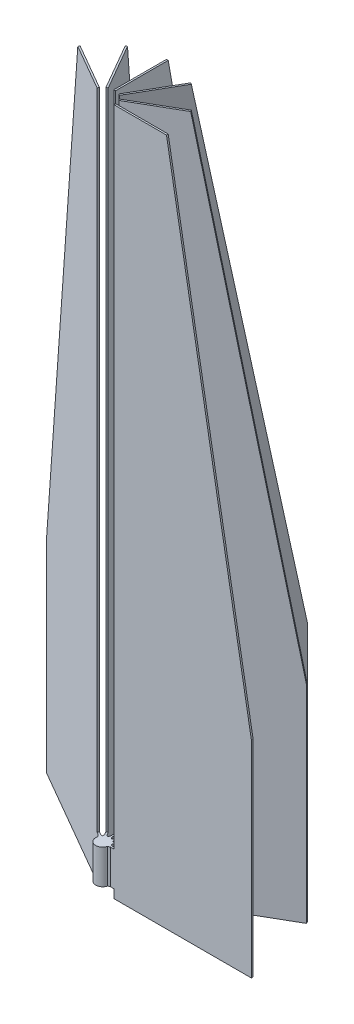
SolidWorks part; units mm, degrees
material "自定义塑料"
ref_plane "前视基准面" through (0, 0, 0) normal (0, 0, 1) x (1, 0, 0)
ref_plane "上视基准面" through (0, 0, 0) normal (0, 1, 0) x (1, 0, 0)
ref_plane "右视基准面" through (0, 0, 0) normal (1, 0, 0) x (0, 0, -1)
other "Configuration Table"
sketch "Sketch1" plane through (0, 0, 0) normal (0, 0, 1) x (1, 0, 0)
  line L0 (0, 0) -> (0, 20)
  line L1 (0, 20) -> (2, 20)
  line L2 (2, 20) -> (2, 395)
  line L3 (2, 395) -> (32.6284, 395)
  line L4 (32.6284, 395) -> (82, 115)
  line L5 (82, 115) -> (82, -5)
  line L6 (82, -5) -> (2, -5)
  line L7 (2, -5) -> (2, 0)
  line L8 (2, 0) -> (0, 0)
  point P11 (1, 0)
  dimension "D1" = 20
  dimension "D2" = 5
  dimension "D3" = 400
  dimension "D4" = 80
  dimension "D5" = 100
  dimension "D6" = 2
  dimension "D7" = 120
extrude "Boss-Extrude1" add sketch "Sketch1" along normal blind 1
sketch "Sketch2" plane through (0, -5, 0) normal (0, -1, 0) x (1, 0, 0)
  line L0 (0, 1) -> (0, 0) construction
  line L1 (0, 1) -> (2, 1) construction
  circle A0 centre (-5, 0.5) radius 4
  dimension "D1" = 8
  dimension "D2" = 5
  dimension "D3" = 0.5
extrude "Boss-Extrude2" add sketch "Sketch2" against normal blind 20 from surface at -5 separate body starting at face at (1, 0, 0.5)
sketch "Sketch3" plane through (0, 0, 0) normal (0, -1, 0) x (1, 0, 0)
  line L0 (0, 1) -> (-1.1363, 1.5353)
  line L1 (0, 0) -> (0, 1)
  line L2 (0, 0) -> (-1.1363, -0.5353)
  line L3 (-5, 0.5) -> (0, 0.5) construction
  line L4 (-1.1363, 1.5353) -> (-5, 0.5) construction
  line L5 (-5, 0.5) -> (-1.1363, -0.5353) construction
  arc A0 (-1.1363, -0.5353) -> (-1.1363, 1.5353) centre (-5, 0.5) ccw
  dimension "D1" = 15
  dimension "D2" = 15
extrude "Boss-Extrude3" add sketch "Sketch3" against normal blind 20
pattern_circular "CirPattern1" count 6 every 30 about axis through (-5, 0, 0.5) along (0, 1, 0) of "Boss-Extrude3"
pattern_circular "CirPattern2" count 7 every 30 about axis through (-5, 0, 0.5) along (0, 1, 0) of "Boss-Extrude1"
